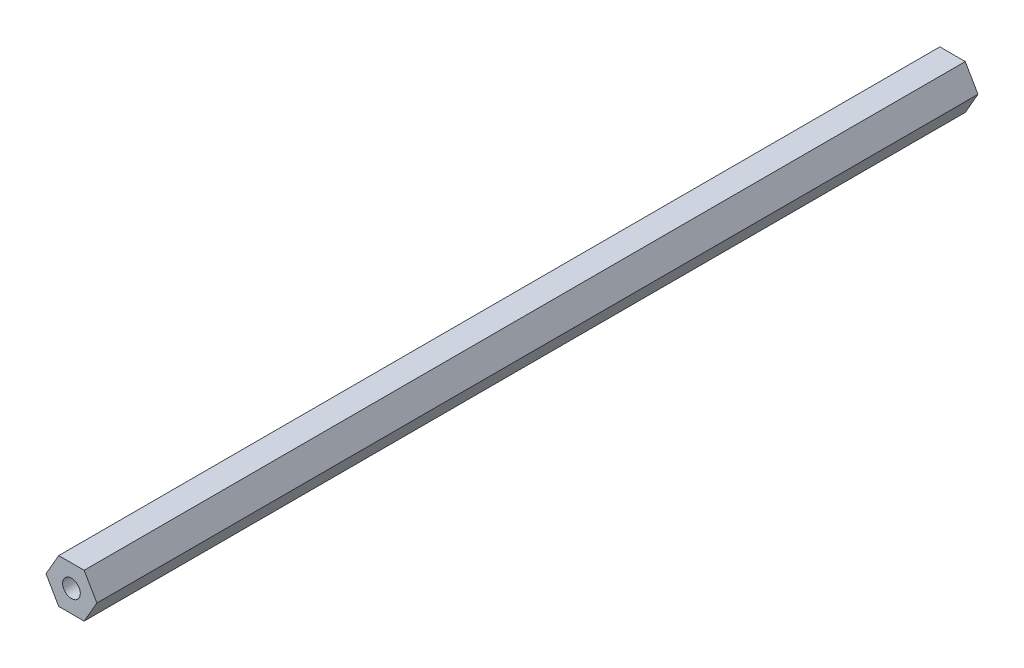
SolidWorks part; units mm, degrees
material "6061-T6 (SS)"
ref_plane "Front Plane" through (0, 0, 0) normal (0, 0, 1) x (1, 0, 0)
ref_plane "Top Plane" through (0, 0, 0) normal (0, 1, 0) x (1, 0, 0)
ref_plane "Right Plane" through (0, 0, 0) normal (1, 0, 0) x (0, 0, -1)
sketch "Sketch1" plane through (0, 0, 0) normal (0, 0, 1) x (1, 0, 0)
  line L1 (7.3323, 0) -> (3.6662, 6.35)
  line L2 (3.6662, 6.35) -> (-3.6662, 6.35)
  line L3 (-3.6662, 6.35) -> (-7.3323, 0)
  line L4 (-7.3323, 0) -> (-3.6662, -6.35)
  line L5 (-3.6662, -6.35) -> (3.6662, -6.35)
  line L6 (3.6662, -6.35) -> (7.3323, 0)
  circle A0 centre (0, 0) radius 6.35 construction
  circle A1 centre (0, 0) radius 2.5527
  dimension "D1" = 12.7
  dimension "D2" = 5.1054
extrude "Boss-Extrude1" add sketch "Sketch1" along normal blind 254
